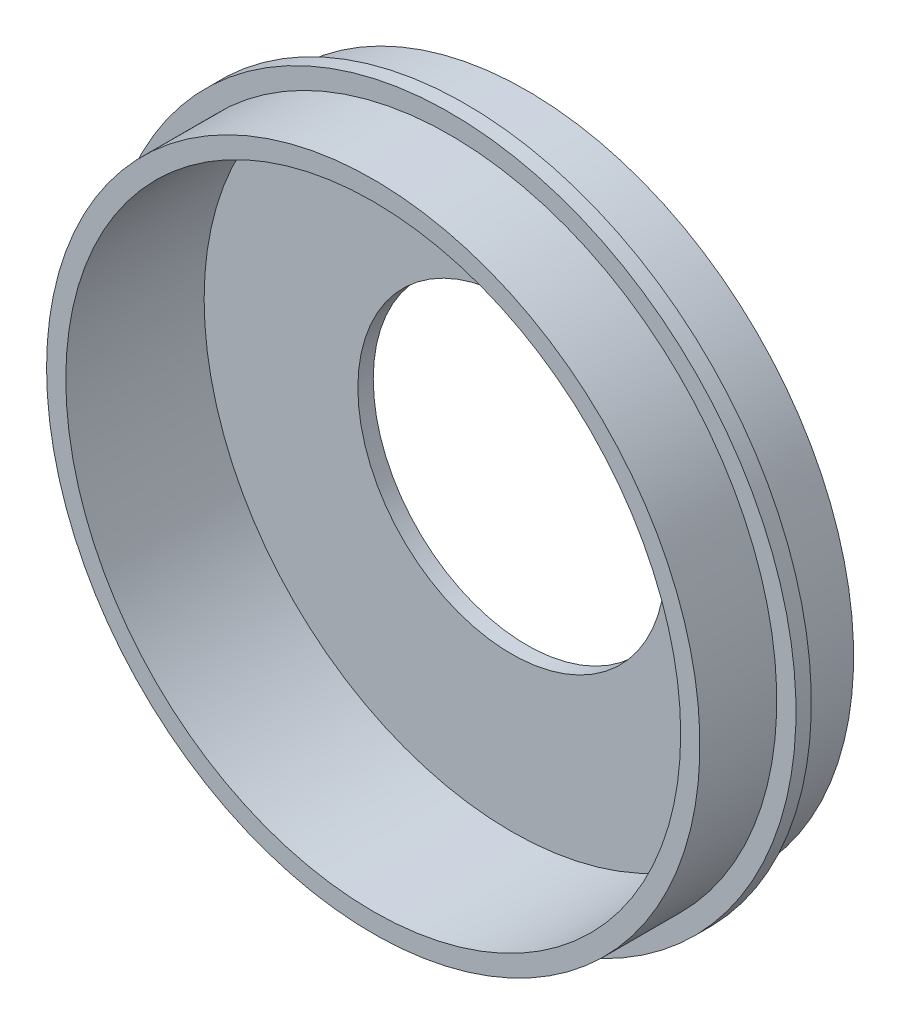
SolidWorks part; units mm, degrees
ref_plane "Front Plane" through (0, 0, 0) normal (0, 0, 1) x (1, 0, 0)
ref_plane "Top Plane" through (0, 0, 0) normal (0, 1, 0) x (1, 0, 0)
ref_plane "Right Plane" through (0, 0, 0) normal (1, 0, 0) x (0, 0, -1)
sketch "Sketch6" plane through (0, 0, 0) normal (1, 0, 0) x (0, 0, -1)
  line L0 (0, 0) -> (-40.103, 0) construction
  line L1 (0, 0) -> (0, 25.4) construction
  line L2 (0, 25.4) -> (-2.54, 25.4)
  line L3 (-2.54, 25.4) -> (-2.54, 50.8)
  line L4 (-2.54, 50.8) -> (-25.4, 50.8)
  line L5 (-25.4, 50.8) -> (-25.4, 53.975)
  line L6 (-25.4, 53.975) -> (-12.7, 53.975)
  line L7 (-12.7, 53.975) -> (-12.7, 57.15)
  line L8 (-12.7, 57.15) -> (-10.16, 57.15)
  line L9 (-10.16, 57.15) -> (-10.16, 53.975)
  line L10 (-10.16, 53.975) -> (0, 53.975)
  line L11 (0, 53.975) -> (0, 25.4)
  dimension "D1" = 28.575
  dimension "D2" = 25.4
  dimension "D3" = 25.4
  dimension "D4" = 22.86
  dimension "D5" = 3.175
  dimension "D6" = 3.175
  dimension "D7" = 2.54
  dimension "D8" = 12.7
revolve "Revolve1" add sketch "Sketch6" angle 360 about L0
